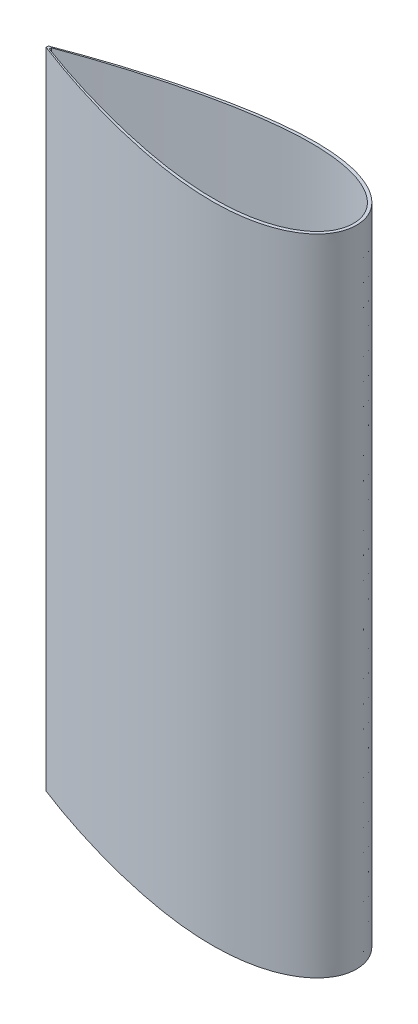
SolidWorks part; units mm, degrees
ref_plane "Front Plane" through (0, 0, 0) normal (0, 0, 1) x (1, 0, 0)
ref_plane "Top Plane" through (0, 0, 0) normal (0, 1, 0) x (1, 0, 0)
ref_plane "Right Plane" through (0, 0, 0) normal (1, 0, 0) x (0, 0, -1)
sketch "Sketch1" plane through (0, 0, 0) normal (0, 1, 0) x (1, 0, 0)
  line L0 (-57.12, 0.2856) -> (-57.12, -0.2856)
  spline S0 degree 3 poles (-57.12, 0.2856) (-57.0455, 0.3146) (-56.7485, 0.4302) (-56.0834, 0.6872) (-54.983, 1.1069) (-53.4592, 1.6767) (-51.5286, 2.3805) (-49.2122, 3.1993) (-46.5354, 4.1122) (-43.5275, 5.0973) (-40.2216, 6.1319) (-36.6538, 7.1928) (-32.8633, 8.2563) (-28.8918, 9.2976) (-24.7825, 10.2906) (-20.5805, 11.2078) (-16.3315, 12.0203) (-12.0818, 12.6984) (-7.8773, 13.2128) (-3.7637, 13.5358) (0.2146, 13.643) (4.0146, 13.5152) (7.5949, 13.1401) (10.9169, 12.5129) (13.9444, 11.6373) (16.6449, 10.5244) (18.9894, 9.1915) (20.9528, 7.6595) (22.5125, 5.9499) (23.6467, 4.0833) (24.3334, 2.0809) (24.5534, 0) (24.3334, -2.0809) (23.6467, -4.0833) (22.5125, -5.9499) (20.9528, -7.6595) (18.9894, -9.1915) (16.6449, -10.5244) (13.9444, -11.6373) (10.9169, -12.5129) (7.5949, -13.1401) (4.0146, -13.5152) (0.2146, -13.643) (-3.7637, -13.5358) (-7.8773, -13.2128) (-12.0818, -12.6984) (-16.3315, -12.0203) (-20.5805, -11.2078) (-24.7825, -10.2906) (-28.8918, -9.2976) (-32.8633, -8.2563) (-36.6538, -7.1928) (-40.2216, -6.1319) (-43.5275, -5.0973) (-46.5354, -4.1122) (-49.2122, -3.1993) (-51.5286, -2.3805) (-53.4592, -1.6767) (-54.983, -1.1069) (-56.0834, -0.6872) (-56.7485, -0.4302) (-57.0455, -0.3146) (-57.12, -0.2856) knots 0 0 0 0 0.001336 0.005324 0.011911 0.02101 0.032502 0.04624 0.062053 0.079747 0.099113 0.11992 0.141927 0.164877 0.188507 0.212545 0.23672 0.260766 0.284425 0.307464 0.329673 0.350875 0.370935 0.389754 0.407278 0.423494 0.438437 0.452195 0.464929 0.476888 0.488429 0.5 0.511571 0.523112 0.535071 0.547805 0.561563 0.576506 0.592722 0.610246 0.629065 0.649125 0.670327 0.692536 0.715575 0.739234 0.76328 0.787455 0.811493 0.835123 0.858073 0.88008 0.900887 0.920253 0.937947 0.95376 0.967498 0.97899 0.988089 0.994676 0.998664 1 1 1 1
extrude "Boss-Extrude1" add sketch "Sketch1" along normal blind 170
sketch "Sketch2" plane through (0, 0, 0) normal (0, 1, 0) x (1, 0, 0)
  line L0 (-56.32, 0.2688) -> (-56.32, -0.2688)
  spline S0 degree 3 poles (-56.32, 0.2688) (-56.247, 0.2961) (-55.9558, 0.4049) (-55.3037, 0.6468) (-54.2248, 1.0418) (-52.7308, 1.5781) (-50.8379, 2.2406) (-48.5669, 3.0112) (-45.9425, 3.8705) (-42.9936, 4.7976) (-39.7524, 5.7714) (-36.2545, 6.7699) (-32.5383, 7.7708) (-28.6445, 8.7509) (-24.6158, 9.6854) (-20.4961, 10.5487) (-16.3304, 11.3133) (-12.164, 11.9516) (-8.0422, 12.4357) (-4.0094, 12.7396) (-0.1096, 12.8404) (3.6152, 12.7202) (7.1244, 12.3673) (10.3802, 11.7774) (13.3472, 10.9539) (15.9936, 9.9075) (18.2913, 8.6544) (20.216, 7.2141) (21.746, 5.6063) (22.86, 3.8494) (23.5355, 1.9624) (23.7522, 0) (23.5355, -1.9624) (22.86, -3.8494) (21.746, -5.6063) (20.216, -7.2141) (18.2913, -8.6544) (15.9936, -9.9075) (13.3472, -10.9539) (10.3802, -11.7774) (7.1244, -12.3673) (3.6152, -12.7202) (-0.1096, -12.8404) (-4.0094, -12.7396) (-8.0422, -12.4357) (-12.164, -11.9516) (-16.3304, -11.3133) (-20.4961, -10.5487) (-24.6158, -9.6854) (-28.6445, -8.7509) (-32.5383, -7.7708) (-36.2545, -6.7699) (-39.7524, -5.7714) (-42.9936, -4.7976) (-45.9425, -3.8705) (-48.5669, -3.0112) (-50.8379, -2.2406) (-52.7308, -1.5781) (-54.2248, -1.0418) (-55.3037, -0.6468) (-55.9558, -0.4049) (-56.247, -0.2961) (-56.32, -0.2688) knots 0 0 0 0 0.001336 0.005327 0.011918 0.021024 0.032528 0.046283 0.06212 0.079847 0.099254 0.120113 0.14218 0.165202 0.188914 0.213046 0.237324 0.261482 0.285262 0.308426 0.33076 0.352081 0.372245 0.391144 0.408713 0.424926 0.439806 0.453432 0.465957 0.477632 0.488823 0.5 0.511177 0.522368 0.534043 0.546568 0.560194 0.575074 0.591287 0.608856 0.627755 0.647919 0.66924 0.691574 0.714738 0.738518 0.762676 0.786954 0.811086 0.834798 0.85782 0.879887 0.900746 0.920153 0.93788 0.953717 0.967472 0.978976 0.988082 0.994673 0.998664 1 1 1 1
extrude "Cut-Extrude1" cut sketch "Sketch2" against normal through all and the other way through all
